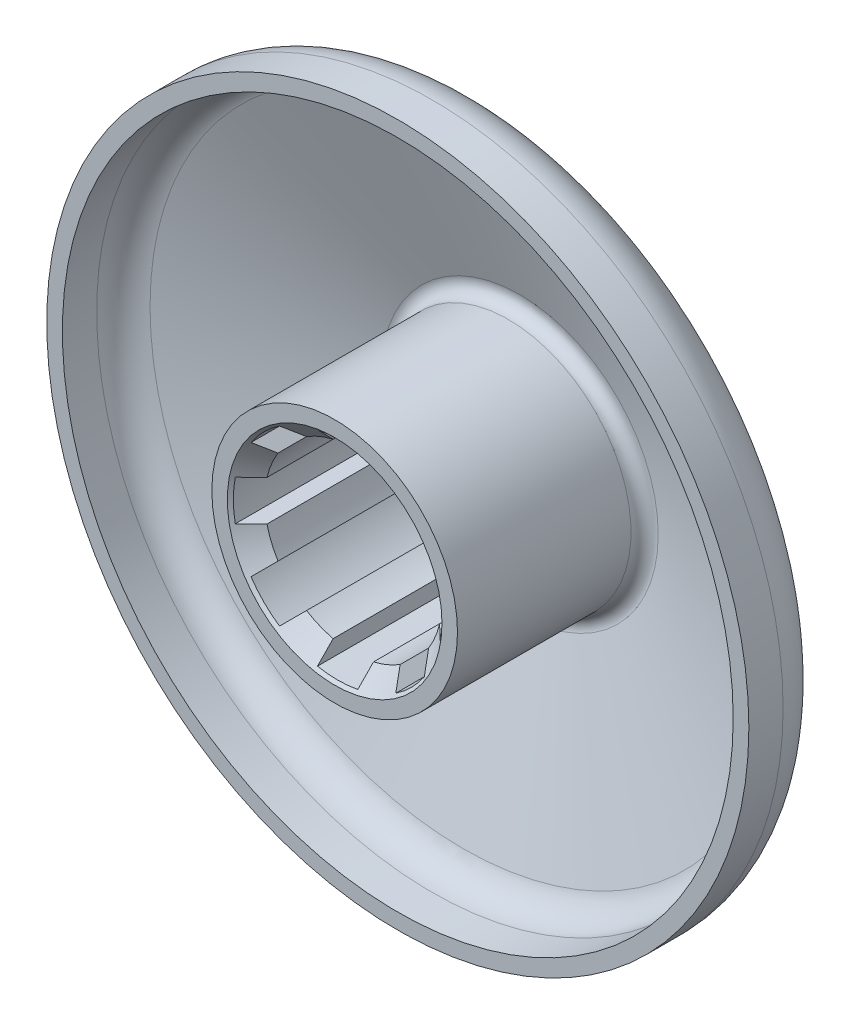
SolidWorks part; units mm, degrees
ref_plane "Front Plane" through (0, 0, 0) normal (0, 0, 1) x (1, 0, 0)
ref_plane "Top Plane" through (0, 0, 0) normal (0, 1, 0) x (1, 0, 0)
ref_plane "Right Plane" through (0, 0, 0) normal (1, 0, 0) x (0, 0, -1)
sketch "Sketch1" plane through (0, 0, 0) normal (0, 0, 1) x (1, 0, 0)
  circle A0 centre (0, 0) radius 14.725
  circle A1 centre (0, 0) radius 20.4
  dimension "D1" = 29.45
  dimension "D2" = 40.8
extrude "Boss-Extrude1" add sketch "Sketch1" along normal blind 34.3
sketch "Sketch3" plane through (0, 0, 0) normal (0, 1, 0) x (1, 0, 0)
  line L0 (-20.4, 0) -> (-58.3, -12.3145)
  line L1 (-58.3, -12.3145) -> (-58.3, -23.8145)
  line L2 (0, 0) -> (0, 11.6188) construction
  line L4 (-20.4, -2.7338) -> (-55.7, -14.2035)
  line L5 (-55.7, -14.2035) -> (-55.7, -23.8145)
  line L6 (-20.4, 0) -> (-20.4, -2.7338)
  line L7 (-19.5966, -2.4727) -> (-55.7, -14.2035) construction
  line L8 (-58.3, -23.8145) -> (-55.7, -23.8145)
  line L10 (14.725, 0) -> (-14.725, 0) construction
  dimension "D1" = 116.6
  dimension "D2" = 11.5
  dimension "D3" = 18
  dimension "D4" = 2.6
revolve "Revolve1" add sketch "Sketch3" angle 360 about L2
fillet "Fillet1" radius 8 1 edges at (58.3, 0, 12.3145)
fillet "Fillet2" radius 5.4 1 edges at (55.7, 0, 14.2035)
sketch "Sketch4" plane through (0, 0, 0) normal (0, 0, -1) x (-1, 0, 0)
  line L0 (0, 0) -> (0, 4.3955) construction
  line L1 (-3.35, 14.3389) -> (-3.35, 16.998)
  line L2 (3.35, 14.3389) -> (3.35, 16.998)
  arc A0 (3.35, 16.998) -> (-3.35, 16.998) centre (0, 0) ccw
  circle A1 centre (0, 0) radius 14.725 construction
  arc A2 (3.35, 14.3389) -> (-3.35, 14.3389) centre (0, 0) ccw
  dimension "D1" = 34.65
  dimension "D2" = 6.7
extrude "Cut-Extrude1" cut sketch "Sketch4" against normal through all
pattern_circular "CirPattern1" count 8 over 360 about axis through (0, 0, 0) along (0, 0, 1) of "Cut-Extrude1"
fillet "Fillet3" radius 10 1 edges at (20.4, 0, 0)
sketch "Sketch5" plane through (0, 0, 0) normal (0, 1, 0) x (1, 0, 0)
  line L0 (-17.325, -34.3) -> (-17.325, -33.8)
  line L1 (-17.325, 0) -> (-17.325, -34.3) construction
  line L2 (-17.325, -34.3) -> (-17.825, -34.3)
  line L3 (-17.825, -34.3) -> (-17.325, -33.8)
  line L4 (-17.325, -33.8) -> (-13.825, -30.3)
  line L5 (-13.825, -30.3) -> (-13.825, -34.3)
  line L6 (-17.325, -34.3) -> (-13.825, -34.3)
  line L7 (0, 0) -> (0, 12.8013) construction
  dimension "D1" = 0.5
  dimension "D2" = 0.5
  dimension "D3" = 4
revolve "Cut-Revolve1" cut sketch "Sketch5" angle 360 about L7
chamfer "Chamfer1" distance 1 angle 45 8 edges at (13.6041, 5.635, 0) (13.6041, -5.635, 0) (5.635, -13.6041, 0) (-5.635, -13.6041, 0) (-13.6041, -5.635, 0) (-13.6041, 5.635, 0) (-5.635, 13.6041, 0) (5.635, 13.6041, 0)
fillet "Fillet4" radius 2 1 edges at (20.4, 0, 2.7338)
fillet "Fillet5" [suppressed] radius 0.5
chamfer "Chamfer2" [suppressed] distance 1 angle 45
